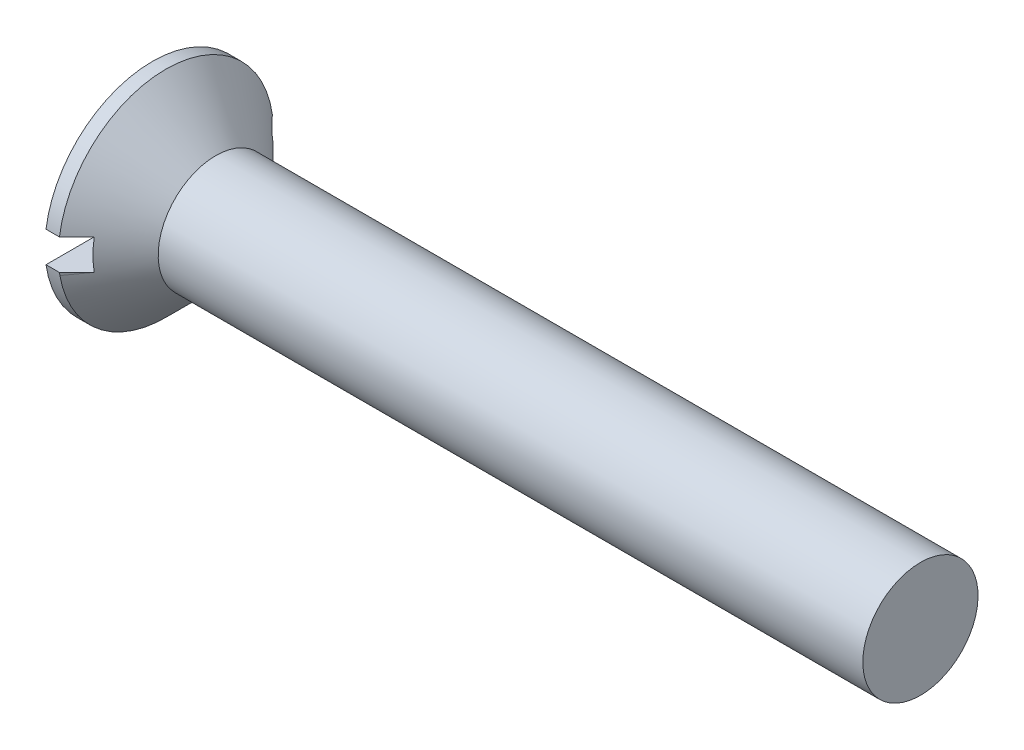
SolidWorks part; units mm, degrees
material "Plain Carbon Steel"
ref_plane "Front Plane" through (0, 0, 0) normal (0, 0, 1) x (1, 0, 0)
ref_plane "Top Plane" through (0, 0, 0) normal (0, 1, 0) x (1, 0, 0)
ref_plane "Right Plane" through (0, 0, 0) normal (1, 0, 0) x (0, 0, -1)
sketch "Sketch1" plane through (0, 0, 0) normal (0, 0, 1) x (1, 0, 0)
  line L0 (0, 0) -> (0, 2.8)
  line L1 (0, 2.8) -> (0.35, 2.8)
  line L2 (0.35, 2.8) -> (1.65, 1.5)
  line L3 (1.65, 1.5) -> (20, 1.5)
  line L4 (20, 1.5) -> (20, 0)
  line L5 (20, 0) -> (0, 0) construction
  line L6 (0, 0) -> (20, 0)
  dimension "D1" = 45
  dimension "D2" = 3
  dimension "D3" = 5.6
  dimension "D4" = 1.65
  dimension "D5" = 20
revolve "Revolve1" add sketch "Sketch1" angle 360 about L5
sketch "Sketch2" plane through (0, 0, 0) normal (-1, 0, 0) x (0, 0, 1)
  line L0 (2.8, 0) -> (-2.8, 0) construction
  line L1 (-2.8, 0.4) -> (2.8, 0.4)
  line L2 (-2.8, 0.4) -> (-2.8, -0.4)
  line L3 (-2.8, -0.4) -> (2.8, -0.4)
  line L4 (2.8, 0.4) -> (2.8, -0.4)
  circle A0 centre (0, 0) radius 2.8 construction
  dimension "D1" = 0.8
extrude "Cut-Extrude1" cut sketch "Sketch2" against normal blind 0.8
